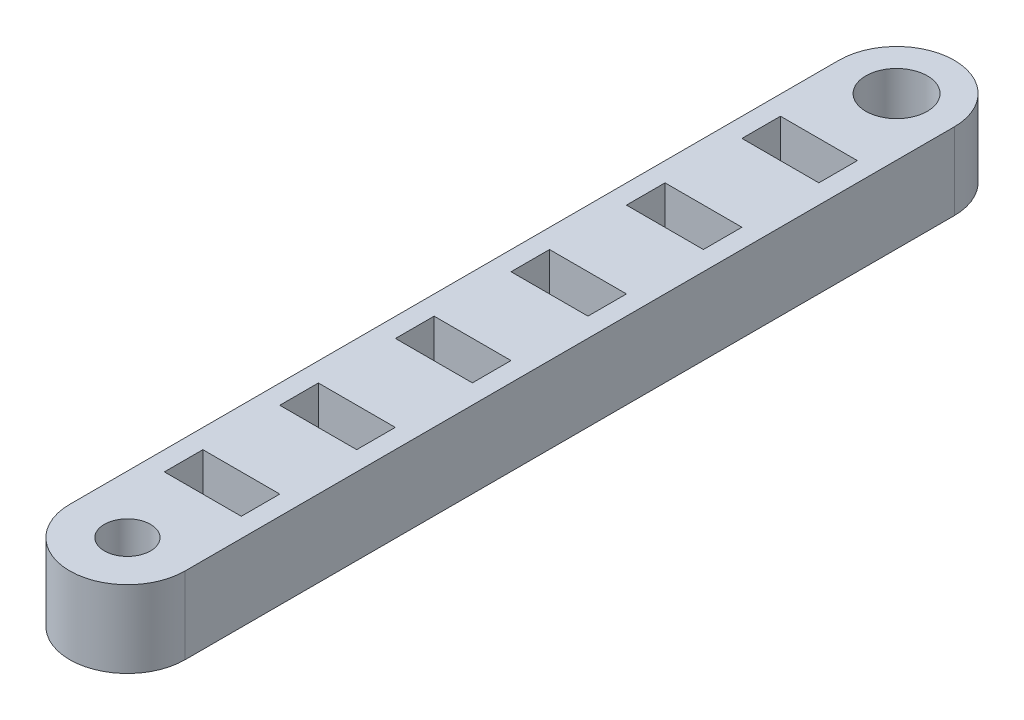
SolidWorks part; units mm, degrees
ref_plane "Front Plane" through (0, 0, 0) normal (0, 0, 1) x (1, 0, 0)
ref_plane "Top Plane" through (0, 0, 0) normal (0, 1, 0) x (1, 0, 0)
ref_plane "Right Plane" through (0, 0, 0) normal (1, 0, 0) x (0, 0, -1)
sketch "Sketch1" plane through (0, 0, 0) normal (0, 1, 0) x (1, 0, 0)
  line L0 (5.4308, 63.6644) -> (5.4308, -36.3356) construction
  line L1 (12.9308, 63.6644) -> (12.9308, -36.3356)
  line L2 (-2.0692, 63.6644) -> (-2.0692, -36.3356)
  arc A0 (12.9308, 63.6644) -> (-2.0692, 63.6644) centre (5.4308, 63.6644) ccw
  arc A1 (-2.0692, -36.3356) -> (12.9308, -36.3356) centre (5.4308, -36.3356) ccw
  point P2 (5.4308, 13.6644)
extrude "Boss-Extrude1" add sketch "Sketch1" along normal blind 10
sketch "Sketch2" plane through (0, 10, 0) normal (0, 1, 0) x (1, 0, 0)
  line L0 (5.4308, 63.6644) -> (5.4308, -36.3356) construction
  circle A1 centre (5.4308, -36.3356) radius 3
sketch "Sketch8" plane through (0, 10, 0) normal (0, 1, 0) x (1, 0, 0)
  line L0 (5.4308, 71.1644) -> (5.4308, 63.6644)
  arc A0 (12.9308, 63.6644) -> (-2.0692, 63.6644) centre (5.4308, 63.6644) ccw construction
  circle A1 centre (5.4308, 63.6644) radius 4
extrude "Cut-Extrude3" cut sketch "Sketch8" against normal blind 22
sketch "Sketch14" plane through (0, 10, 0) normal (0, 1, 0) x (1, 0, 0)
  line L0 (5.4308, 63.6644) -> (5.4308, 53.5685)
  line L1 (5.4308, 63.6644) -> (5.4308, -36.3356) construction
  line L2 (5.4308, 53.5685) -> (10.4308, 53.5685)
  line L3 (5.4308, 53.5685) -> (0.4308, 53.5685)
  line L4 (5.4308, 48.5609) -> (5.4308, 38.5609)
  line L5 (10.4308, 53.5685) -> (0.4308, 53.5685)
  line L6 (10.4308, 53.5685) -> (10.4308, 48.5609)
  line L7 (10.4308, 48.5609) -> (0.4308, 48.5609)
  line L8 (0.4308, 53.5685) -> (0.4308, 48.5609)
  line L9 (5.4308, 38.5609) -> (10.4308, 38.5609)
  line L10 (5.4308, 38.5609) -> (0.4308, 38.5609)
  line L11 (5.4308, 33.5445) -> (5.4308, 23.5445)
  line L12 (10.4308, 38.5609) -> (0.4308, 38.5609)
  line L13 (10.4308, 38.5609) -> (10.4308, 33.5445)
  line L14 (10.4308, 33.5445) -> (0.4308, 33.5445)
  line L15 (0.4308, 38.5609) -> (0.4308, 33.5445)
  line L16 (5.4308, 23.5445) -> (10.4308, 23.5445)
  line L17 (5.4308, 23.5445) -> (0.4308, 23.5445)
  line L18 (5.4308, 18.5387) -> (5.4308, 8.5387)
  line L19 (10.4308, 23.5445) -> (0.4308, 23.5445)
  line L20 (10.4308, 23.5445) -> (10.4308, 18.5387)
  line L21 (10.4308, 18.5387) -> (0.4308, 18.5387)
  line L22 (0.4308, 23.5445) -> (0.4308, 18.5387)
  line L23 (5.4308, 8.5387) -> (10.4308, 8.5387)
  line L24 (5.4308, 8.5387) -> (0.4308, 8.5387)
  line L25 (5.4308, 3.5126) -> (5.4308, -6.5098)
  line L26 (10.4308, 8.5387) -> (0.4308, 8.5387)
  line L27 (10.4308, 8.5387) -> (10.4308, 3.5126)
  line L28 (10.4308, 3.5126) -> (0.4308, 3.5126)
  line L29 (0.4308, 8.5387) -> (0.4308, 3.5126)
  line L30 (5.4308, -6.5098) -> (10.4308, -6.5098)
  line L31 (5.4308, -6.5098) -> (0.4308, -6.5098)
  line L32 (5.4308, -11.5272) -> (5.4308, -21.5272)
  line L33 (10.4308, -6.5098) -> (0.4308, -6.5098)
  line L34 (10.4308, -6.5098) -> (10.4308, -11.5272)
  line L35 (10.4308, -11.5272) -> (0.4308, -11.5272)
  line L36 (0.4308, -6.5098) -> (0.4308, -11.5272)
  line L37 (5.4308, -21.5272) -> (10.4308, -21.5272)
  line L38 (5.4308, -21.5272) -> (0.4308, -21.5272)
  line L40 (10.4308, -21.5272) -> (0.4308, -21.5272)
  line L41 (10.4308, -21.5272) -> (10.4308, -26.5314)
  line L42 (10.4308, -26.5314) -> (0.4308, -26.5314)
  line L43 (0.4308, -21.5272) -> (0.4308, -26.5314)
  circle A0 centre (5.4308, -36.3356) radius 3
extrude "Cut-Extrude4" cut sketch "Sketch14" against normal blind 20 contours A0 | L38 L43 L42 L41 L37 | L31 L36 L35 L34 L30 | L24 L29 L28 L27 L23 | L17 L22 L21 L20 L16 | L10 L15 L14 L13 L9 | L3 L8 L7 L6 L2
